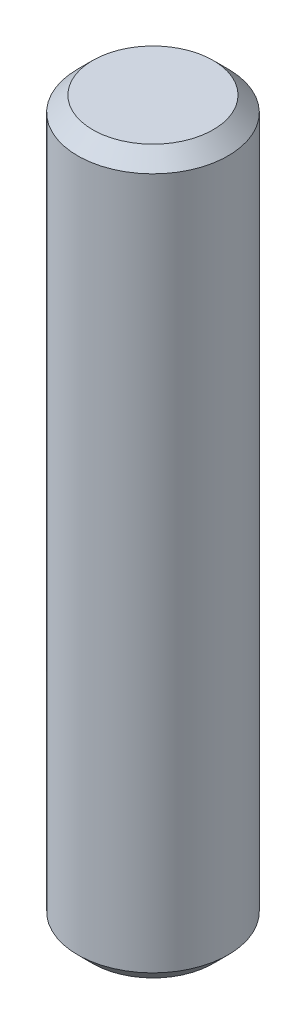
SolidWorks part; units mm, degrees
ref_plane "Plan de face" through (0, 0, 0) normal (0, 0, 1) x (1, 0, 0)
ref_plane "Plan de dessus" through (0, 0, 0) normal (0, 1, 0) x (1, 0, 0)
ref_plane "Plan de droite" through (0, 0, 0) normal (1, 0, 0) x (0, 0, -1)
sketch "Esquisse1" plane through (0, 0, 0) normal (0, 0, 1) x (1, 0, 0)
  line L0 (0, 0) -> (-4, 0)
  line L1 (-4, 0) -> (-5, 1)
  line L2 (-5, 1) -> (-5, 47)
  line L3 (-5, 47) -> (-4, 48)
  line L4 (-4, 48) -> (0, 48)
  line L5 (0, 48) -> (0, 0)
  line L6 (-4, 53.5454) -> (-4, -7.1256) construction
  dimension "D1" = 48
  dimension "D2" = 5
  dimension "D3" = 4
  dimension "D4" = 135
  dimension "D5" = 135
revolve "Révolution1" add sketch "Esquisse1" angle 360 about L5
